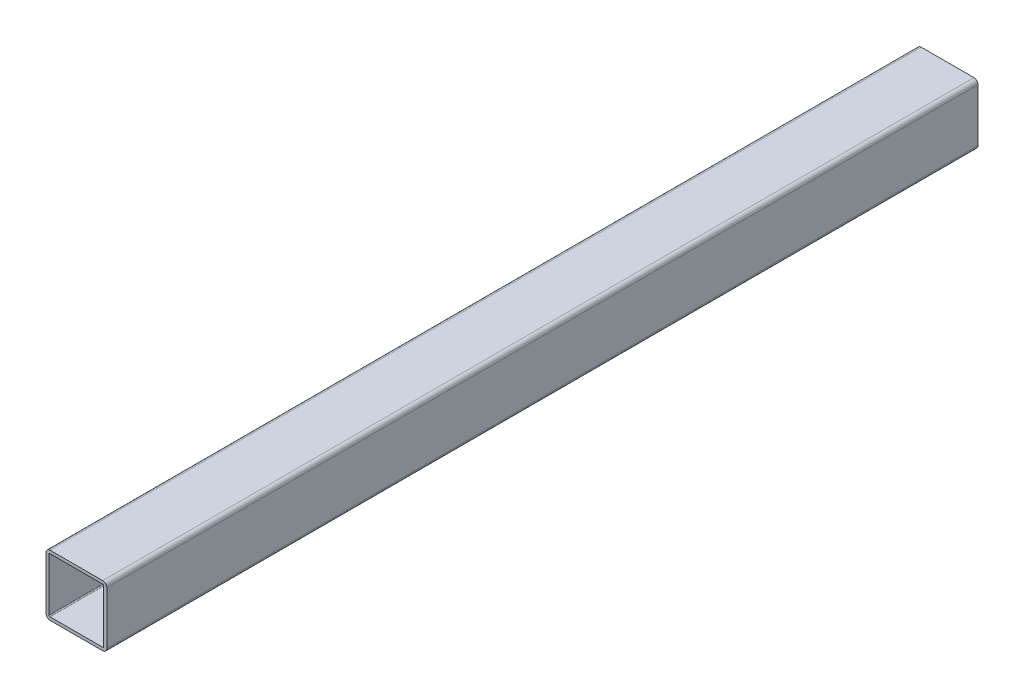
SolidWorks part; units mm, degrees
ref_plane "Спереди" through (0, 0, 0) normal (0, 0, 1) x (1, 0, 0)
ref_plane "Сверху" through (0, 0, 0) normal (0, 1, 0) x (1, 0, 0)
ref_plane "Справа" through (0, 0, 0) normal (1, 0, 0) x (0, 0, -1)
sketch "Эскиз1" plane through (0, 0, 0) normal (0, 0, 1) x (1, 0, 0)
  line L1 (2, 0) -> (28, 0)
  line L2 (0, 2) -> (0, 28)
  line L3 (2, 30) -> (28, 30)
  line L4 (30, 2) -> (30, 28)
  arc A0 (0, 2) -> (2, 0) centre (2, 2) ccw
  arc A1 (30, 2) -> (28, 0) centre (28, 2) cw
  arc A2 (28, 30) -> (30, 28) centre (28, 28) cw
  arc A3 (2, 30) -> (0, 28) centre (2, 28) ccw
  point P7 (0, 0)
  dimension "D3" = 2
  dimension "D1" = 30
  dimension "D2" = 30
extrude "Вытянуть-Тонкостенный1" add sketch "Эскиз1" along normal blind 430 thin thin type one direction reverse wall 1.5
